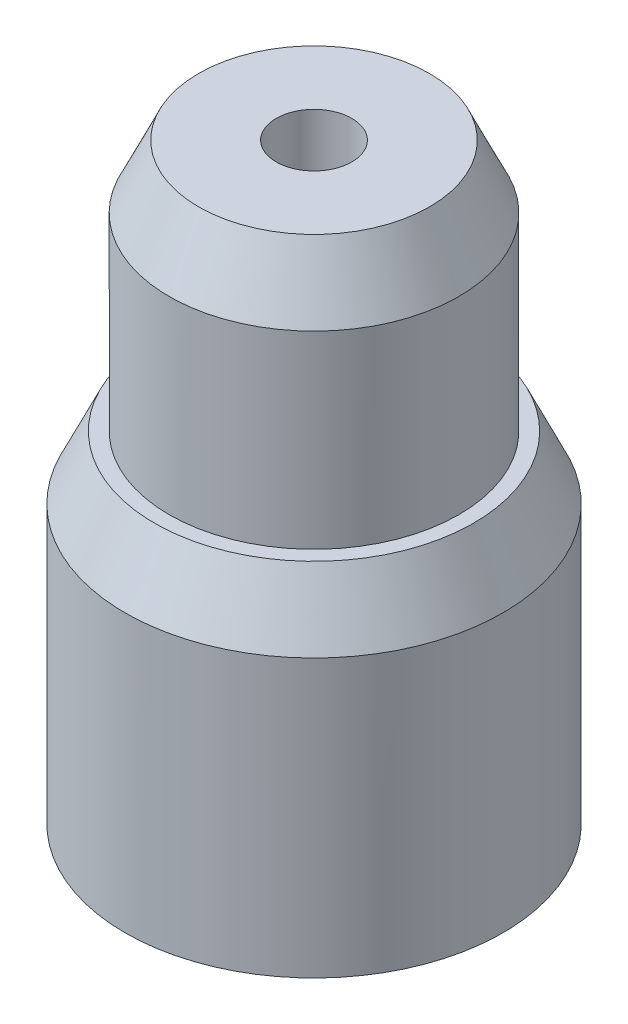
SolidWorks part; units mm, degrees
ref_plane "Alzado" through (0, 0, 0) normal (0, 0, 1) x (1, 0, 0)
ref_plane "Planta" through (0, 0, 0) normal (0, 1, 0) x (1, 0, 0)
ref_plane "Vista lateral" through (0, 0, 0) normal (1, 0, 0) x (0, 0, -1)
sketch "Croquis1" plane through (0, 0, 0) normal (0, 1, 0) x (1, 0, 0)
  circle A0 centre (0, 0) radius 15
  dimension "D1" = 30
extrude "Saliente-Extruir1" add sketch "Croquis1" along normal blind 27
sketch "Croquis2" plane through (0, 27, 0) normal (0, 1, 0) x (1, 0, 0)
  circle A0 centre (0, 0) radius 11.5
  dimension "D1" = 23
extrude "Saliente-Extruir2" add sketch "Croquis2" along normal blind 20
chamfer "Chaflán1" distance 5 angle 25 1 edges at (0, 47, 11.5)
chamfer "Chaflán2" distance 5 angle 25 1 edges at (0, 27, 15)
sketch "Croquis3" plane through (0, 0, 0) normal (0, -1, 0) x (-1, 0, 0)
  circle A0 centre (0, 0) radius 5
extrude "Cortar-Extruir1" cut sketch "Croquis3" against normal blind 10
sketch "Croquis4" plane through (0, 47, 0) normal (0, 1, 0) x (1, 0, 0)
  circle A0 centre (0, 0) radius 3
extrude "Cortar-Extruir2" cut sketch "Croquis4" against normal blind 10
